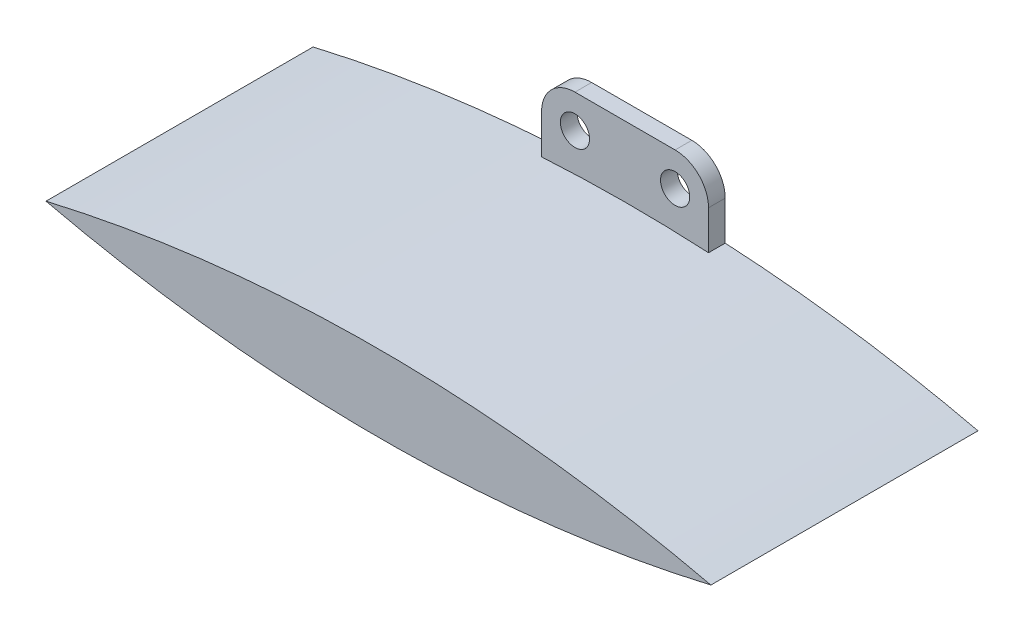
SolidWorks part; units mm, degrees
ref_plane "Plan de face" through (0, 0, 0) normal (0, 0, 1) x (1, 0, 0)
ref_plane "Plan de dessus" through (0, 0, 0) normal (0, 1, 0) x (1, 0, 0)
ref_plane "Plan de droite" through (0, 0, 0) normal (1, 0, 0) x (0, 0, -1)
sketch "Esquisse1" plane through (0, 0, 0) normal (0, 0, 1) x (1, 0, 0)
  line L0 (-13.285, -0.2956) -> (-13.285, -5.0164)
  line L1 (-9.285, 12.9836) -> (2.715, 12.9836) construction
  line L2 (-9.285, 12.9836) -> (-9.285, -5.0164) construction
  line L3 (-9.285, -5.0164) -> (2.715, -5.0164) construction
  line L4 (2.715, 12.9836) -> (2.715, -5.0164) construction
  line L5 (-9.285, 16.9836) -> (2.715, 16.9836)
  line L6 (-13.285, 12.9836) -> (-13.285, 8.2628)
  line L7 (-9.285, -9.0164) -> (2.715, -9.0164)
  line L8 (6.715, 12.9836) -> (6.715, 8.3152)
  line L9 (-42.6532, 3.9836) -> (-13.285, 3.9836) construction
  line L10 (-9.285, 3.9836) -> (-13.285, 3.9836) construction
  line L11 (-9.285, 3.9836) -> (36.9987, 3.9836) construction
  line L12 (6.715, -0.348) -> (6.715, -5.0164)
  circle A0 centre (-9.285, 12.9836) radius 1.75
  circle A1 centre (-9.285, -5.0164) radius 1.75
  circle A2 centre (2.715, -5.0164) radius 1.75
  circle A3 centre (2.715, 12.9836) radius 1.75
  arc A4 (-9.285, 16.9836) -> (-13.285, 12.9836) centre (-9.285, 12.9836) ccw
  arc A5 (6.715, 12.9836) -> (2.715, 16.9836) centre (2.715, 12.9836) ccw
  arc A6 (2.715, -9.0164) -> (6.715, -5.0164) centre (2.715, -5.0164) ccw
  arc A7 (-13.285, -5.0164) -> (-9.285, -9.0164) centre (-9.285, -5.0164) ccw
  arc A8 (36.9987, 3.9836) -> (6.715, 8.3152) centre (-2.8272, -166.4244) ccw
  arc A9 (-42.6532, 3.9836) -> (-13.285, -0.2956) centre (-2.8272, 174.3916) ccw
  arc A10 (-13.285, 8.2628) -> (-42.6532, 3.9836) centre (-2.8272, -166.4244) ccw
  arc A11 (6.715, -0.348) -> (36.9987, 3.9836) centre (-2.8272, 174.3916) ccw
  dimension "D1" = 3.5
  dimension "D2" = 3.5
  dimension "D3" = 3.5
  dimension "D4" = 3.5
  dimension "D7" = 8
  dimension "D8" = 8
  dimension "D9" = 8
  dimension "D10" = 8
  dimension "D11" = 350
  dimension "D12" = 350
  dimension "D5" = 18
  dimension "D6" = 12
extrude "Boss.-Extru.1" add sketch "Esquisse1" along normal blind 2
sketch "Esquisse2" plane through (0, 0, 2) normal (0, 0, 1) x (1, 0, 0)
  line L0 (-42.6532, 3.9836) -> (36.9987, 3.9836) construction
  arc A0 (36.9987, 3.9836) -> (-42.6532, 3.9836) centre (-2.8272, -166.4244) ccw
  arc A1 (-42.6532, 3.9836) -> (36.9987, 3.9836) centre (-2.8272, 174.3916) ccw
extrude "Boss.-Extru.2" add sketch "Esquisse2" along normal blind 30
